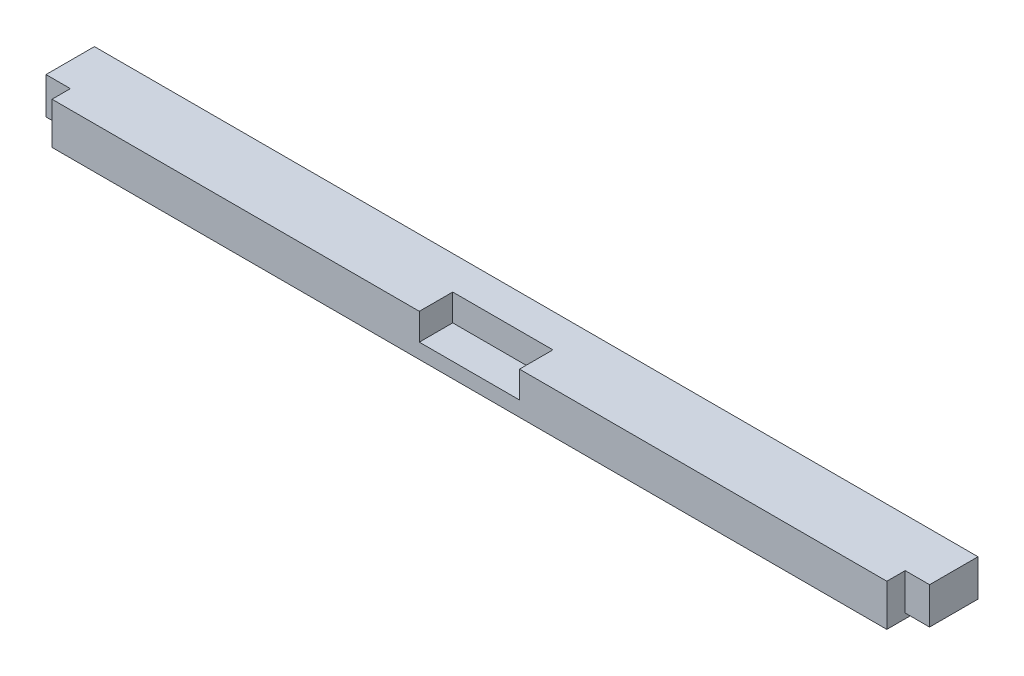
SolidWorks part; units mm, degrees
ref_plane "Front Plane" through (0, 0, 0) normal (0, 0, 1) x (1, 0, 0)
ref_plane "Top Plane" through (0, 0, 0) normal (0, 1, 0) x (1, 0, 0)
ref_plane "Right Plane" through (0, 0, 0) normal (1, 0, 0) x (0, 0, -1)
sketch "Sketch1" plane through (0, 0, 0) normal (0, 1, 0) x (1, 0, 0)
  line L1 (0, 50.8) -> (635, 50.8)
  line L2 (0, 50.8) -> (0, 0)
  line L3 (0, 0) -> (635, 0)
  line L4 (635, 50.8) -> (635, 0)
extrude "Boss-Extrude1" add sketch "Sketch1" along normal blind 31.75
sketch "Sketch2" plane through (635, 0, 0) normal (1, 0, 0) x (0, 0, -1)
  line L1 (50.8, 31.75) -> (13.97, 31.75)
  line L2 (50.8, 31.75) -> (50.8, 3.81)
  line L3 (50.8, 3.81) -> (13.97, 3.81)
  line L4 (13.97, 31.75) -> (13.97, 3.81)
extrude "Boss-Extrude2" add sketch "Sketch2" along normal blind 18.542
sketch "Sketch3" plane through (0, 0, 0) normal (-1, 0, 0) x (0, 0, 1)
  line L1 (-50.8, 31.75) -> (-13.97, 31.75)
  line L2 (-50.8, 31.75) -> (-50.8, 3.81)
  line L3 (-50.8, 3.81) -> (-13.97, 3.81)
  line L4 (-13.97, 31.75) -> (-13.97, 3.81)
extrude "Boss-Extrude3" add sketch "Sketch3" along normal blind 18.542
sketch "Sketch4" plane through (0, 31.75, 0) normal (0, 1, 0) x (1, 0, 0)
  line L1 (355.6, 25.4) -> (279.4, 25.4)
  line L2 (355.6, 25.4) -> (355.6, 0)
  line L3 (355.6, 0) -> (279.4, 0)
  line L4 (279.4, 25.4) -> (279.4, 0)
  line L5 (355.6, 25.4) -> (279.4, 0) construction
  line L6 (355.6, 0) -> (279.4, 25.4) construction
  point P0 (317.5, 12.7)
extrude "Cut-Extrude1" cut sketch "Sketch4" against normal blind 20.32
